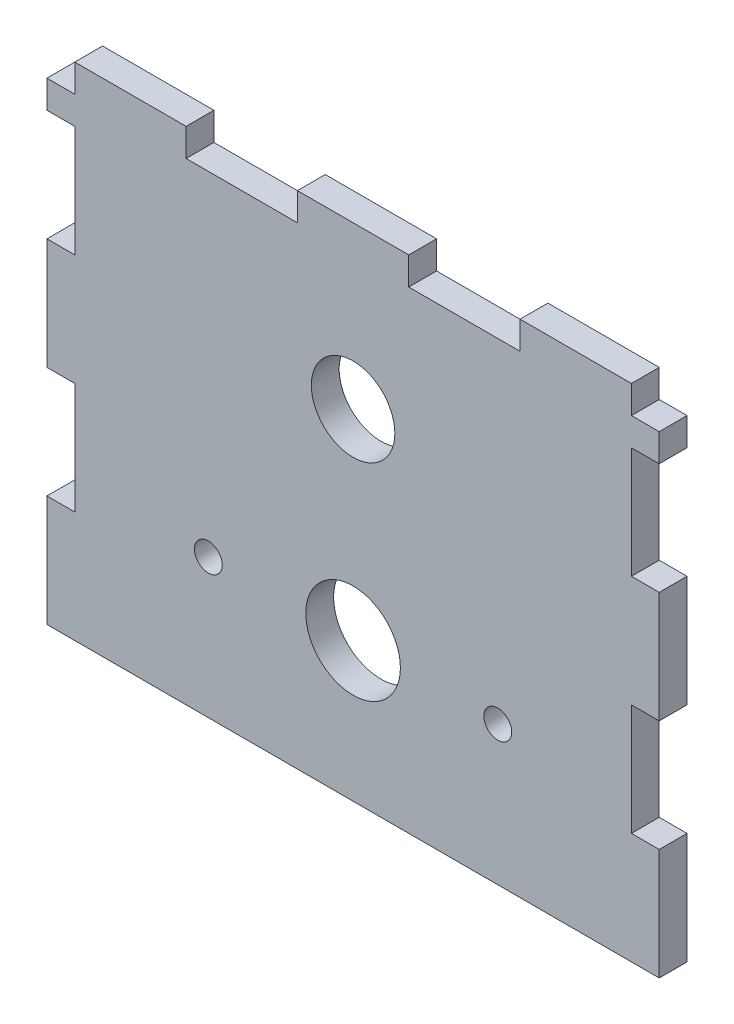
SolidWorks part; units mm, degrees
ref_plane "정면" through (0, 0, 0) normal (0, 0, 1) x (1, 0, 0)
ref_plane "윗면" through (0, 0, 0) normal (0, 1, 0) x (1, 0, 0)
ref_plane "우측면" through (0, 0, 0) normal (1, 0, 0) x (0, 0, -1)
sketch "스케치1" plane through (0, 0, 0) normal (0, 0, 1) x (1, 0, 0)
  line L0 (-37.7239, -17.5) -> (33.9157, -17.5) construction
  line L1 (-50, 42.5) -> (50, 42.5)
  line L2 (-50, 42.5) -> (-50, -42.5)
  line L3 (-50, -42.5) -> (50, -42.5)
  line L4 (50, 42.5) -> (50, -42.5)
  line L5 (0, 64.1622) -> (0, -63.9316) construction
  line L6 (-59.9758, 0) -> (56.5335, 0) construction
  circle A1 centre (0, -17.5) radius 8.5
  circle A2 centre (-26, -17.5) radius 2.5
  circle A3 centre (26, -17.5) radius 2.5
  circle A4 centre (0, 18.5) radius 7.5
  point P20 (0, 0)
  point P21 (0, 0)
  dimension "D3" = 17
  dimension "D4" = 5
  dimension "D5" = 25
  dimension "D8" = 15
  dimension "D1" = 85
  dimension "D2" = 100
  dimension "D6" = 26
  dimension "D7" = 26
  dimension "D9" = 36
extrude "보스-돌출1" add sketch "스케치1" along normal blind 5
sketch "스케치2" plane through (0, 0, 5) normal (0, 0, 1) x (1, 0, 0)
  line L1 (50, -42.5) -> (55, -42.5)
  line L2 (50, -42.5) -> (50, -22.5)
  line L3 (50, -22.5) -> (55, -22.5)
  line L4 (55, -42.5) -> (55, -22.5)
  dimension "D1" = 5
  dimension "D2" = 20
extrude "보스-돌출2" add sketch "스케치2" against normal up to surface (5 mm away) up to face at (0, 0, 0)
mirror "대칭 복사1" about plane through (0, 0, 0) normal (1, 0, 0) of "보스-돌출2"
pattern_linear "선형 패턴1" count 2 spacing 40 along (0, 1, 0) of "대칭 복사1", "보스-돌출2"
sketch "스케치3" plane through (0, 0, 5) normal (0, 0, 1) x (1, 0, 0)
  line L0 (0, 51.0513) -> (0, 21.4102) construction
  line L1 (50, 42.5) -> (-50, 42.5) construction
  line L2 (-10, 42.5) -> (10, 42.5)
  line L3 (-10, 42.5) -> (-10, 47.5)
  line L4 (-10, 47.5) -> (10, 47.5)
  line L5 (10, 42.5) -> (10, 47.5)
  dimension "D1" = 5
  dimension "D2" = 20
extrude "보스-돌출3" add sketch "스케치3" against normal up to surface (5 mm away) up to face at (0, -1.875, 0)
pattern_linear "선형 패턴2" count 2 spacing 40 along (1, 0, 0) of "보스-돌출3"
pattern_linear "선형 패턴3" count 2 spacing 40 along (-1, 0, 0) of "보스-돌출3"
sketch "스케치5" plane through (0, 0, 5) normal (0, 0, 1) x (1, 0, 0)
  line L0 (50, 17.5) -> (50, 47.5) construction
  line L1 (50, 42.5) -> (55, 42.5)
  line L2 (50, 42.5) -> (50, 37.5)
  line L3 (50, 37.5) -> (55, 37.5)
  line L4 (55, 42.5) -> (55, 37.5)
  line L5 (30, 42.5) -> (10, 42.5) construction
  dimension "D1" = 5
  dimension "D2" = 5
extrude "보스-돌출4" add sketch "스케치5" against normal up to surface (5 mm away) up to face at (0, 14.1667, 0)
mirror "대칭 복사2" about plane through (0, 0, 0) normal (1, 0, 0) of "보스-돌출4"
